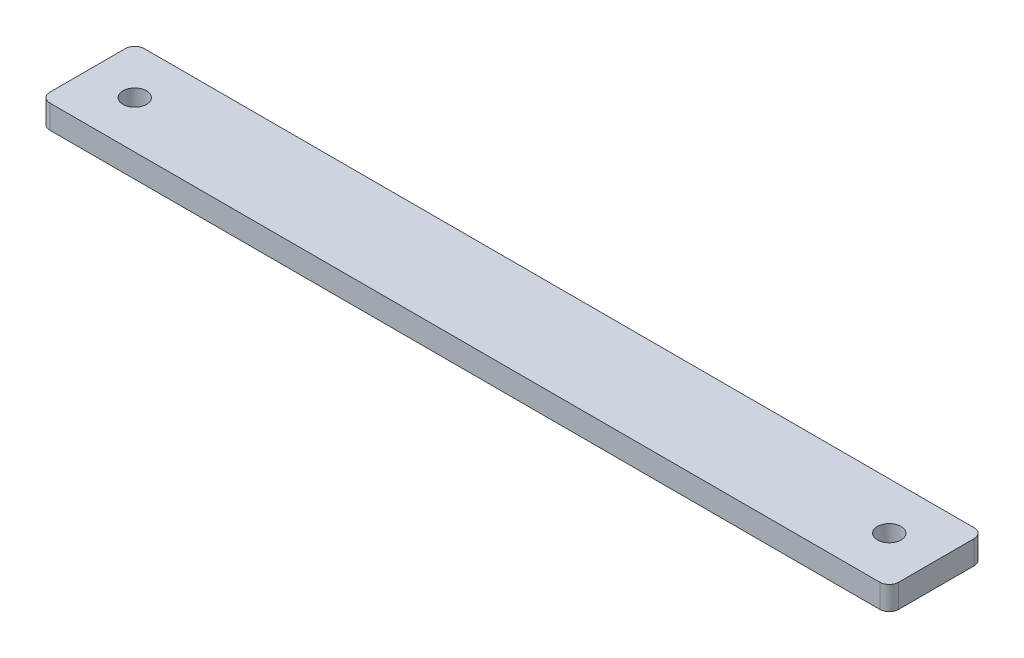
SolidWorks part; units mm, degrees
ref_plane "Front Plane" through (0, 0, 0) normal (0, 0, 1) x (1, 0, 0)
ref_plane "Top Plane" through (0, 0, 0) normal (0, 1, 0) x (1, 0, 0)
ref_plane "Right Plane" through (0, 0, 0) normal (1, 0, 0) x (0, 0, -1)
sketch "Sketch1" plane through (0, 0, 0) normal (0, 1, 0) x (1, 0, 0)
  line L1 (0, 0) -> (228.6, 0)
  line L2 (0, 0) -> (0, 25.4)
  line L3 (0, 25.4) -> (228.6, 25.4)
  line L4 (228.6, 0) -> (228.6, 25.4)
  dimension "D1" = 228.6
  dimension "D2" = 25.4
extrude "Boss-Extrude1" add sketch "Sketch1" along normal blind 6.35
sketch "Sketch2" plane through (0, 6.35, 0) normal (0, 1, 0) x (1, 0, 0)
  line L1 (0, 25.4) -> (0, 0) construction
  line L2 (0, 12.7) -> (228.6, 12.7) construction
  line L3 (228.6, 0) -> (228.6, 25.4) construction
  circle A0 centre (12.7, 12.7) radius 3.175
  circle A1 centre (215.9, 12.7) radius 3.175
  dimension "D1" = 203.2
  dimension "D2" = 12.7
  dimension "D3" = 6.35
extrude "Cut-Extrude1" cut sketch "Sketch2" against normal through all and the other way through all
fillet "Fillet1" radius 2.54 4 edges at (228.6, 3.175, 0) (228.6, 3.175, -25.4) (0, 3.175, -25.4) (0, 3.175, 0)
